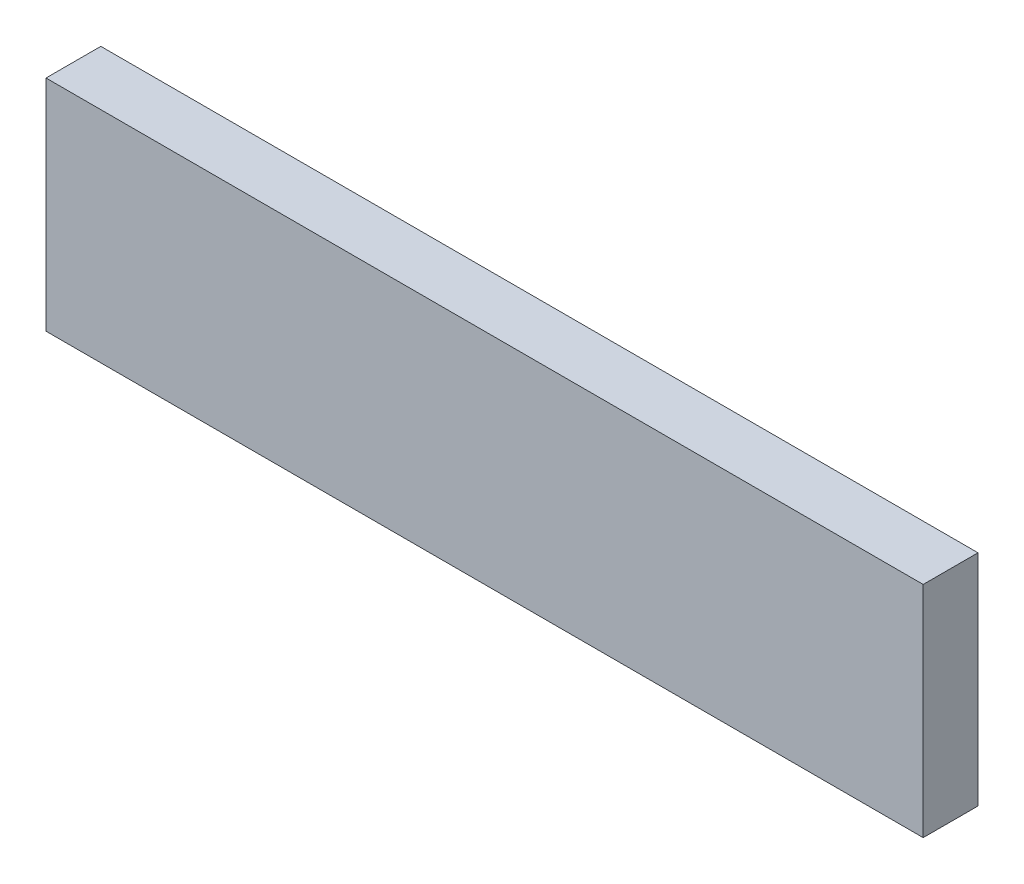
SolidWorks part; units mm, degrees
ref_plane "Front Plane" through (0, 0, 0) normal (0, 0, 1) x (1, 0, 0)
ref_plane "Top Plane" through (0, 0, 0) normal (0, 1, 0) x (1, 0, 0)
ref_plane "Right Plane" through (0, 0, 0) normal (1, 0, 0) x (0, 0, -1)
sketch "Sketch1" plane through (0, 0, 0) normal (0, 0, 1) x (1, 0, 0)
  line L1 (0, 0) -> (40, 0)
  line L2 (0, 0) -> (0, 10)
  line L3 (0, 10) -> (40, 10)
  line L4 (40, 0) -> (40, 10)
  dimension "D1" = 40
  dimension "D2" = 10
extrude "Boss-Extrude1" add sketch "Sketch1" along normal blind 2.5
sketch "Sketch2" plane through (0, 0, 0) normal (0, -1, 0) x (1, 0, 0)
  arc A0 (43.2082, 1.7936) -> (37.1498, 5.1394) centre (38.509, 0.4427) ccw construction
  arc A1 (44.4104, 2.1392) -> (36.8021, 6.3411) centre (38.509, 0.4427) ccw
  arc A2 (42.0059, 1.448) -> (37.4976, 3.9378) centre (38.509, 0.4427) ccw
  arc A3 (42.0059, 1.448) -> (44.4104, 2.1392) centre (43.2082, 1.7936) ccw
  arc A4 (36.8021, 6.3411) -> (37.4976, 3.9378) centre (37.1498, 5.1394) ccw
  arc A5 (45.3715, 2.4155) -> (36.5241, 7.3017) centre (38.509, 0.4427) ccw
  arc A6 (36.5241, 7.3017) -> (37.7756, 2.9772) centre (37.1498, 5.1394) ccw
  arc A7 (41.0448, 1.1717) -> (37.7756, 2.9772) centre (38.509, 0.4427) ccw
  arc A8 (41.0448, 1.1717) -> (45.3715, 2.4155) centre (43.2082, 1.7936) ccw
  point P3 (40.8728, 4.7228)
  point P8 (0, 0)
  point P9 (42.1422, 2.2423)
  point P10 (37.2298, 6.51)
  point P11 (36.3151, 6.8909)
  point P12 (42.0962, 2.282)
  point P13 (37.0325, 5.1115)
  point P14 (43.2082, 1.7936)
  dimension "D1" = 1
